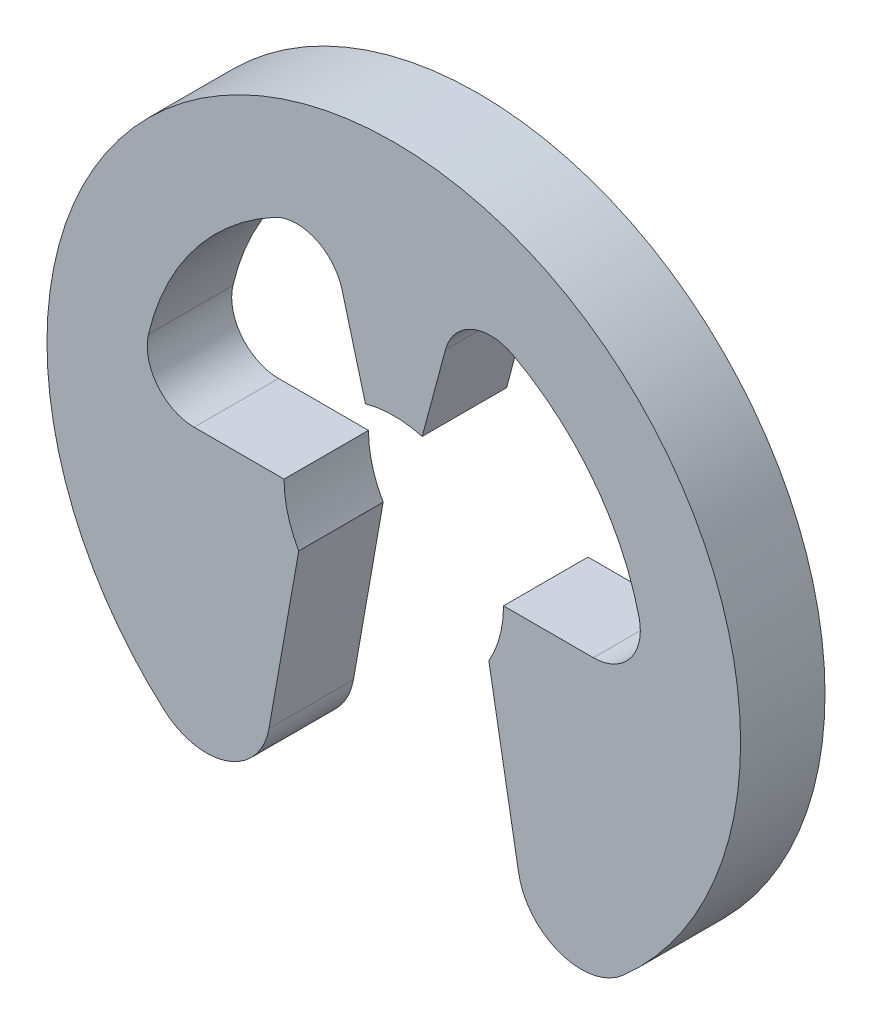
SolidWorks part; units mm, degrees
ref_plane "Plane1" through (0, 0, 0) normal (0, 0, 1) x (1, 0, 0)
ref_plane "Plane2" through (0, 0, 0) normal (0, 1, 0) x (1, 0, 0)
ref_plane "Plane3" through (0, 0, 0) normal (1, 0, 0) x (0, 0, -1)
sketch "Clipboard" plane through (0, 0, 0) normal (0, 0, 1) x (1, 0, 0)
  line L0 (0, 0) -> (0.2853, 0)
  circle A0 centre (0, 0) radius 0.3175
  circle A1 centre (0, 0) radius 1.0033
  dimension "Bridge" = 1.3009
sketch "BodySke" plane through (0, 0, 0) normal (0, 0, 1) x (1, 0, 0)
  line L0 (-0.7581, 0) -> (0.7581, 0) construction
  line L1 (0, 0) -> (0, 0.3302) construction
  line L2 (0, 0) -> (0.1962, 0.7323) construction
  line L3 (0, 0) -> (0.286, -0.1651) construction
  line L4 (0, 0) -> (-0.1962, 0.7323) construction
  line L5 (0, 0) -> (-0.286, -0.1651) construction
  line L6 (0.286, -0.1651) -> (0.3754, -0.6725)
  line L7 (-0.286, -0.1651) -> (-0.3754, -0.6725)
  line L9 (0.3302, 0) -> (0.6005, 0)
  line L10 (-0.3302, 0) -> (-0.6005, 0)
  line L11 (0.0855, 0.3189) -> (0.1554, 0.5801)
  line L12 (-0.0855, 0.3189) -> (-0.1554, 0.5801)
  circle A0 centre (0, 0) radius 0.3302 construction
  arc A1 (0.738, 0.1735) -> (0.3586, 0.6679) centre (0, 0) ccw
  arc A2 (0.6901, -0.7826) -> (-0.6901, -0.7826) centre (0, 0) ccw
  arc A3 (0.286, -0.1651) -> (0.3302, 0) centre (0, 0) ccw
  arc A4 (-0.3586, 0.6679) -> (-0.738, 0.1735) centre (0, 0) ccw
  arc A5 (-0.3302, 0) -> (-0.286, -0.1651) centre (0, 0) ccw
  arc A6 (-0.0855, 0.3189) -> (0.0855, 0.3189) centre (0, 0) cw
  arc A7 (0.3586, 0.6679) -> (0.1554, 0.5801) centre (0.2918, 0.5435) ccw
  arc A8 (0.3754, -0.6725) -> (0.6901, -0.7826) centre (0.5637, -0.6393) ccw
  arc A9 (-0.6901, -0.7826) -> (-0.3754, -0.6725) centre (-0.5637, -0.6393) ccw
  arc A10 (-0.738, 0.1735) -> (-0.6005, 0) centre (-0.6005, 0.1412) ccw
  arc A11 (-0.1554, 0.5801) -> (-0.3586, 0.6679) centre (-0.2918, 0.5435) ccw
  arc A12 (0.6005, 0) -> (0.738, 0.1735) centre (0.6005, 0.1412) ccw
  dimension "OutsideDia" = 11.2798
  dimension "TipRad" = 0.8716
  dimension "CavityDia" = 8.678
  dimension "CavityFilletRad" = 0.644
  dimension "D1" = 30
  dimension "D3" = 30
  dimension "D4" = 20
extrude "Body" add sketch "BodySke" against normal blind 0.254
equation "' \"FreeID@Clipboard\" = 0.025"
equation "' \"Thickness@Body\" = 0.01"
equation "' \"GrooveDia@BodySke\" = 0.026"
equation "' \"FreeOD@Clipboard\" = 0.079"
equation "' \"FreeID@Clipboard\" = 1.213"
equation "' \"Thickness@Body\" = 0.062"
equation "' \"GrooveDia@BodySke\" = 1.23"
equation "' \"FreeOD@Clipboard\" = 1.875"
equation "\"OutsideDia@BodySke\" = ( \"GrooveDia@BodySke\"  /  \"FreeID@Clipboard\" )  * \"FreeOD@Clipboard\""
equation "\"Bridge@Clipboard\" =  (\"OutsideDia@BodySke\" - \"GrooveDia@BodySke\") / 2 * 0.4"
equation "\"CavityDia@BodySke\" = \"OutsideDia@BodySke\"  - 2 * \"Bridge@Clipboard\""
equation "\"CavityFilletRad@BodySke\" =  (\"CavityDia@BodySke\" - \"GrooveDia@BodySke\") / 2 * 0.33"
equation "\"TipRad@BodySke\" = 0.67 * \"Bridge@Clipboard\""
